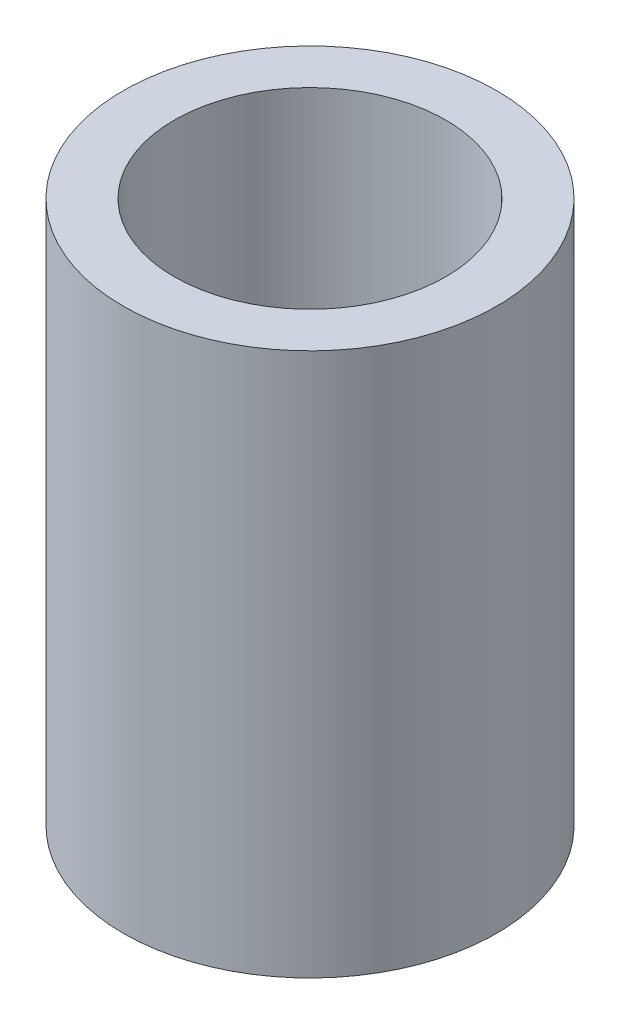
SolidWorks part; units mm, degrees
material "Cobre"
ref_plane "Alzado" through (0, 0, 0) normal (0, 0, 1) x (1, 0, 0)
ref_plane "Planta" through (0, 0, 0) normal (0, 1, 0) x (1, 0, 0)
ref_plane "Vista lateral" through (0, 0, 0) normal (1, 0, 0) x (0, 0, -1)
sketch "Croquis2" plane through (0, 0, 0) normal (0, 1, 0) x (1, 0, 0)
  circle A0 centre (0, 0) radius 5.5
  dimension "D1" = 11
extrude "Saliente-Extruir2" add sketch "Croquis2" along normal blind 16
sketch "Croquis3" plane through (0, 16, 0) normal (0, 1, 0) x (1, 0, 0)
  circle A0 centre (0, 0) radius 4
  dimension "D1" = 8
extrude "Cortar-Extruir1" cut sketch "Croquis3" against normal up to next
